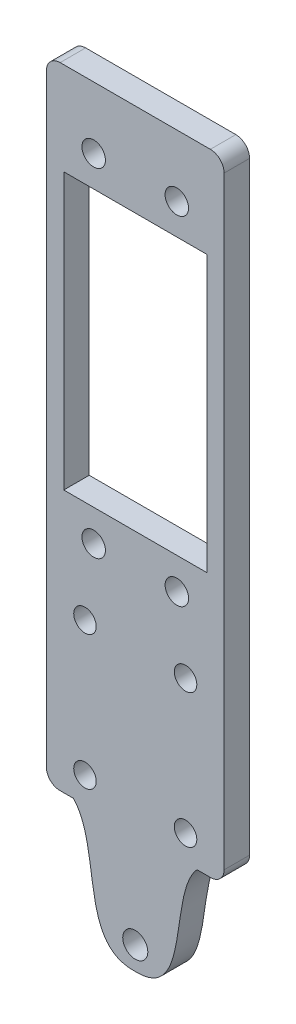
SolidWorks part; units mm, degrees
ref_plane "Front Plane" through (0, 0, 0) normal (0, 0, 1) x (1, 0, 0)
ref_plane "Top Plane" through (0, 0, 0) normal (0, 1, 0) x (1, 0, 0)
ref_plane "Right Plane" through (0, 0, 0) normal (1, 0, 0) x (0, 0, -1)
sketch "Sketch1" plane through (0, 0, 0) normal (0, 0, 1) x (1, 0, 0)
  line L0 (8.585, -14.8799) -> (10.6292, -14.8799)
  line L1 (29.0408, -14.8799) -> (31.085, -14.8799)
  line L2 (13.635, 69.9247) -> (26.035, 69.9247) construction
  line L3 (6.585, -12.8799) -> (6.585, 77.1077)
  line L12 (27.335, -11) -> (12.335, -11) construction
  line L13 (31.085, -14.8799) -> (8.585, -14.8799) construction
  line L14 (33.085, -12.8799) -> (33.085, 77.1077)
  line L15 (31.0356, 79.1571) -> (8.6344, 79.1571)
  line L17 (19.835, -11) -> (19.835, 2.8876) construction
  line L18 (27.335, 9) -> (12.335, 9) construction
  line L19 (9.1712, 24.2234) -> (30.4988, 24.2234)
  line L20 (9.1712, 24.2234) -> (9.1712, 65.3256)
  line L21 (9.1712, 65.3256) -> (30.4988, 65.3256)
  line L22 (30.4988, 24.2234) -> (30.4988, 65.3256)
  line L23 (26.035, 19.5247) -> (13.635, 19.5247) construction
  circle A0 centre (19.835, -29.1815) radius 1.8694
  arc A1 (6.585, 77.1077) -> (8.6344, 79.1571) centre (8.6344, 77.1077) cw
  circle A4 centre (12.335, 9) radius 1.6775
  circle A5 centre (12.335, -11) radius 1.6775
  circle A6 centre (27.335, 9) radius 1.6775
  circle A7 centre (27.335, -11) radius 1.6775
  circle A13 centre (26.035, 69.9247) radius 1.75
  circle A14 centre (13.635, 69.9247) radius 1.75
  circle A15 centre (13.635, 19.5247) radius 1.75
  circle A16 centre (26.035, 19.5247) radius 1.75
  arc A20 (31.085, -14.8799) -> (33.085, -12.8799) centre (31.085, -12.8799) ccw
  arc A21 (8.585, -14.8799) -> (6.585, -12.8799) centre (8.585, -12.8799) cw
  arc A23 (33.085, 77.1077) -> (31.0356, 79.1571) centre (31.0356, 77.1077) ccw
  spline S0 degree 3 poles (10.6292, -14.8799) (14.9457, -19.5983) (11.3308, -32.9123) (19.835, -32.632) knots 0 0 0 0 1 1 1 1
  spline S1 degree 3 poles (29.0408, -14.8799) (24.7243, -19.5983) (28.3392, -32.9123) (19.835, -32.632) knots 0 0 0 0 1 1 1 1
  point P1 (19.835, 9)
  point P16 (19.835, -14.8799)
  point P44 (19.835, 69.9247)
  point P46 (19.835, 65.3256)
  point P48 (19.835, -11)
  point P49 (19.835, 19.5247)
  point P50 (16.2812, 59.3209)
  dimension "D3" = 22.5
  dimension "D4" = 2
  dimension "D10" = 12.4
  dimension "D11" = 3.5
  dimension "D12" = 3.5
  dimension "D13" = 3.5
  dimension "D14" = 3.5
  dimension "D1" = 12.4
  dimension "D2" = 15
  dimension "D5" = 39.1033
  dimension "D7" = 21.3277
  dimension "D8" = 41.1022
  dimension "D9" = 13.8315
extrude "Boss-Extrude1" add sketch "Sketch1" along normal blind 3.8
